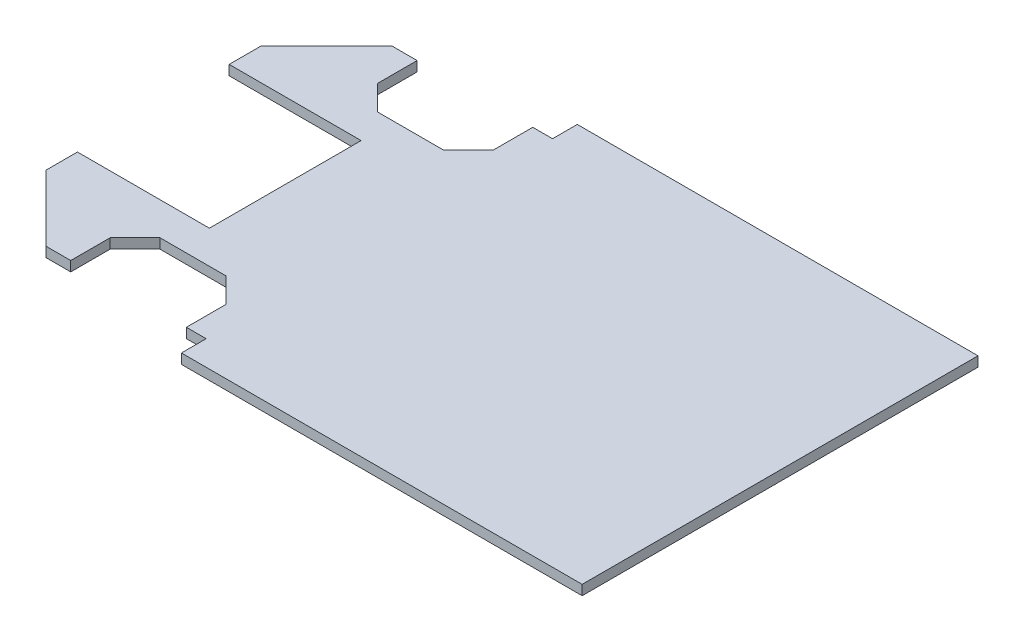
SolidWorks part; units mm, degrees
ref_plane "Front Plane" through (0, 0, 0) normal (0, 0, 1) x (1, 0, 0)
ref_plane "Top Plane" through (0, 0, 0) normal (0, 1, 0) x (1, 0, 0)
ref_plane "Right Plane" through (0, 0, 0) normal (1, 0, 0) x (0, 0, -1)
sketch "Sketch1" plane through (0, 0, 0) normal (0, 1, 0) x (1, 0, 0)
  line L0 (190, 0) -> (0, 0) construction
  line L1 (0, -60) -> (190, -60)
  line L2 (0, -60) -> (0, 60)
  line L3 (0, 60) -> (190, 60)
  line L4 (190, -60) -> (190, 60)
  line L5 (0, -32.5266) -> (19.9734, -52.5)
  line L6 (40, 23) -> (0, 23)
  line L7 (40, 23) -> (40, -23)
  line L8 (40, -23) -> (0, -23)
  line L9 (0, 23) -> (0, -23)
  line L10 (40, 23) -> (0, -23) construction
  line L11 (40, -23) -> (0, 23) construction
  line L12 (19.9734, -52.5) -> (27.4734, -52.5)
  line L13 (68.5266, -52.5) -> (68.5266, -60)
  line L14 (35, -33) -> (27.4734, -40.5266)
  line L15 (27.4734, -52) -> (27.4734, -40.5266) construction
  line L16 (27.4734, -40.5266) -> (27.4734, -52.5)
  line L18 (35, -33) -> (55, -33)
  line L19 (55, -33) -> (62.5266, -40.5266)
  line L20 (62.5266, -52.5) -> (68.5266, -52.5)
  line L21 (47.5, -37) -> (42.5, -37) construction
  line L22 (45, -37) -> (45, -33) construction
  line L23 (45, -56.5) -> (45, -52.5) construction
  line L24 (39.4, -56.5) -> (50.6, -56.5) construction
  line L25 (27.4734, -52.5) -> (62.5266, -52.5) construction
  line L27 (62.5266, -40.5266) -> (62.5266, -52.5)
  line L28 (68.5266, 52.5) -> (68.5266, 60)
  line L29 (62.5266, 52.5) -> (68.5266, 52.5)
  line L31 (62.5266, 40.5266) -> (62.5266, 52.5)
  line L32 (55, 33) -> (62.5266, 40.5266)
  line L33 (35, 33) -> (55, 33)
  line L34 (35, 33) -> (27.4734, 40.5266)
  line L35 (27.4734, 40.5266) -> (27.4734, 52.5)
  line L36 (19.9734, 52.5) -> (27.4734, 52.5)
  line L37 (0, 32.5266) -> (19.9734, 52.5)
  point P7 (0, 0)
  point P8 (20, 0)
  dimension "D1" = 120
  dimension "D2" = 190
  dimension "D3" = 40
  dimension "D4" = 23
  dimension "D5" = 10
  dimension "D6" = 20
  dimension "D7" = 45
  dimension "D8" = 45
  dimension "D9" = 135
  dimension "D10" = 7.5
  dimension "D11" = 6
extrude "Boss-Extrude1" add sketch "Sketch1" along normal blind 3 contours L7 L8 L2 L1 L4 L3 L6
